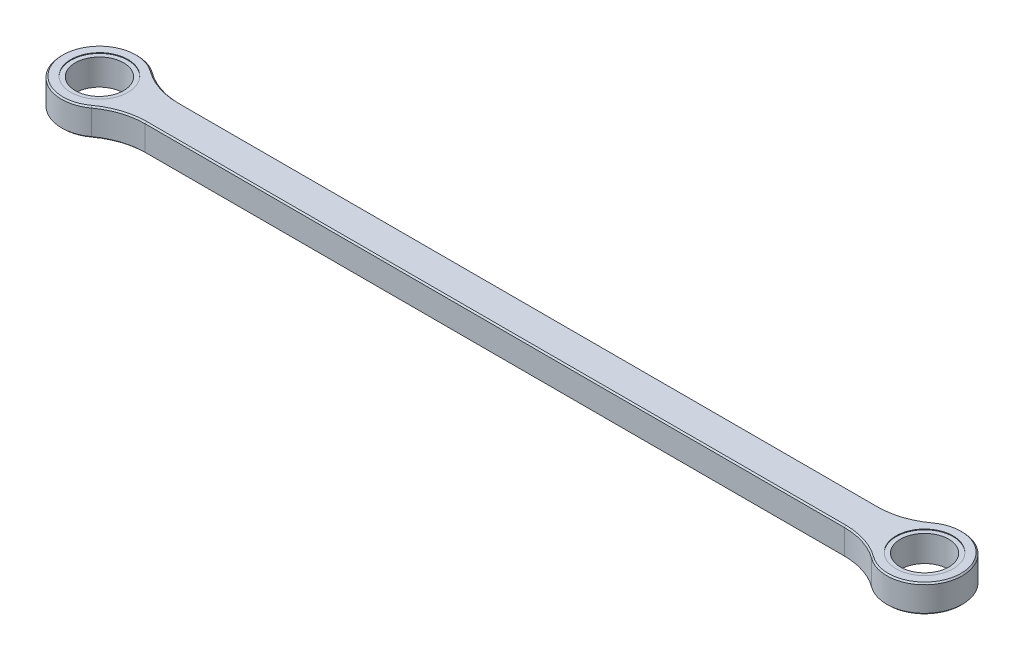
SolidWorks part; units mm, degrees
material "6061 合金"
ref_plane "前视基准面" through (0, 0, 0) normal (0, 0, 1) x (1, 0, 0)
ref_plane "上视基准面" through (0, 0, 0) normal (0, 1, 0) x (1, 0, 0)
ref_plane "右视基准面" through (0, 0, 0) normal (1, 0, 0) x (0, 0, -1)
other "Configuration Table"
sketch "草图1" plane through (0, 0, 0) normal (0, 1, 0) x (1, 0, 0)
  line L0 (0, 0) -> (120, 0) construction
  line L2 (4.899, 2.5) -> (115.101, 2.5)
  line L3 (4.899, 2.5) -> (4.899, -2.5) construction
  line L4 (4.899, -2.5) -> (115.101, -2.5)
  line L5 (115.101, 2.5) -> (115.101, -2.5) construction
  line L6 (60, -2.5) -> (60, 2.5) construction
  line L7 (4.899, 0) -> (115.101, 0) construction
  circle A0 centre (0, 0) radius 5.5 construction
  circle A1 centre (120, 0) radius 5.5 construction
  circle A2 centre (0, 0) radius 3.515
  circle A3 centre (120, 0) radius 3.515
  arc A4 (4.899, 2.5) -> (4.899, -2.5) centre (0, 0) ccw
  arc A5 (115.101, 2.5) -> (115.101, -2.5) centre (120, 0) cw
  point P7 (60, 0)
  dimension "D1" = 11
  dimension "D3" = 11
  dimension "D4" = 7.03
  dimension "D5" = 7.03
  dimension "D2" = 120
  dimension "D6" = 5
extrude "凸台-拉伸1" add sketch "草图1" along normal blind 4
fillet "圆角1" radius 10 4 edges at (115.101, 2, 2.5) (115.101, 2, -2.5) (4.899, 2, 2.5) (4.899, 2, -2.5)
sketch "草图2" plane through (0, 4, 0) normal (0, 1, 0) x (1, 0, 0)
  line L0 (110.8348, 2.5) -> (9.1652, 2.5) construction
  line L1 (9.1652, -2.5) -> (110.8348, -2.5) construction
  line L2 (60, 2.5) -> (60, -2.5) construction
  line L3 (110, 0) -> (10, 0) construction
  line L4 (110, -1.25) -> (10, -1.25)
  line L5 (110, 1.25) -> (10, 1.25)
  arc A6 (110, -1.25) -> (110, 1.25) centre (110, 0) ccw
  arc A7 (10, 1.25) -> (10, -1.25) centre (10, 0) ccw
  point P5 (60, 0)
  dimension "D1" = 50
  dimension "D2" = 2.5
extrude "切除-拉伸1" [suppressed] cut sketch "草图2" against normal blind 2
chamfer "倒角1" distance 0.2 angle 45 16 edges at (60, 0, 2.5) (113.9457, 0, 2.9962) (6.0543, 0, 2.9962) (125.5, 0, 0) (-5.5, 0, 0) (113.9457, 0, -2.9962) (6.0543, 0, -2.9962) (60, 0, -2.5) (60, 4, 2.5) (113.9457, 4, 2.9962) (6.0543, 4, 2.9962) (125.5, 4, 0) (-5.5, 4, 0) (113.9457, 4, -2.9962) (6.0543, 4, -2.9962) (60, 4, -2.5)
sketch "草图3" plane through (0, 4, 0) normal (0, 1, 0) x (1, 0, 0)
  circle A0 centre (0, 0) radius 4.15
  circle A1 centre (120, 0) radius 4.15
  dimension "D1" = 8.3
  dimension "D2" = 8.3
extrude "切除-拉伸2" cut sketch "草图3" against normal blind 0.1
sketch "草图4" plane through (0, 0, 0) normal (0, -1, 0) x (1, 0, 0)
  circle A0 centre (0, 0) radius 4.125
  circle A1 centre (120, 0) radius 4.125
  dimension "D1" = 8.25
  dimension "D2" = 8.25
extrude "切除-拉伸3" cut sketch "草图4" against normal blind 0.1
